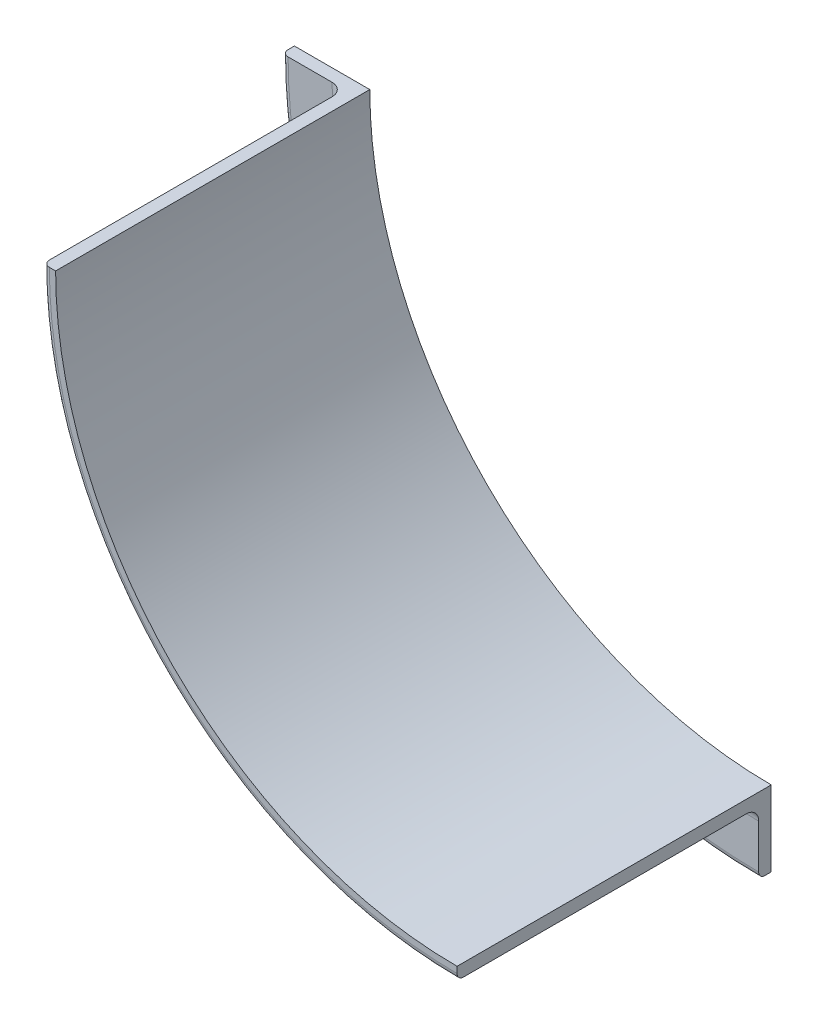
SolidWorks part; units mm, degrees
ref_plane "Front Plane" through (0, 0, 0) normal (0, 0, 1) x (1, 0, 0)
ref_plane "Top Plane" through (0, 0, 0) normal (0, 1, 0) x (1, 0, 0)
ref_plane "Right Plane" through (0, 0, 0) normal (1, 0, 0) x (0, 0, -1)
sketch "Sketch2" plane through (0, 0, 0) normal (0, 0, 1) x (1, 0, 0)
  line L0 (2758.9681, -672.5495) -> (2746.9681, -672.5495)
  line L1 (2822.8581, -736.4395) -> (2822.8581, -748.4395)
  arc A0 (2758.9681, -672.5495) -> (2822.8581, -736.4395) centre (2822.8581, -672.5495) ccw
  arc A1 (2746.9681, -672.5495) -> (2822.8581, -748.4395) centre (2822.8581, -672.5495) ccw
  dimension "D1" = 63.89
  dimension "D2" = 12
  dimension "D3" = 12
extrude "Boss-Extrude1" add sketch "Sketch2" along normal blind 50
sketch "Sketch3" plane through (0, 0, 50) normal (0, 0, 1) x (1, 0, 0)
  line L0 (2758.9681, -672.5495) -> (2746.9681, -672.5495) construction
  line L1 (2822.8581, -748.4395) -> (2822.8581, -736.4395) construction
  line L2 (2756.9681, -672.5495) -> (2737.4788, -672.5495)
  line L3 (2737.4788, -672.5495) -> (2737.4788, -757.5773)
  line L4 (2737.4788, -757.5773) -> (2822.8581, -757.5773)
  line L5 (2822.8581, -757.5773) -> (2822.8581, -738.4395)
  arc A0 (2756.9681, -672.5495) -> (2822.8581, -738.4395) centre (2822.8581, -672.5495) ccw
  dimension "D1" = 65.89
extrude "Cut-Extrude1" cut sketch "Sketch3" against normal blind 48
fillet "Fillet1" radius 1 2 edges at (2769.1958, -726.2118, 2) (2776.2669, -719.1407, 50)
fillet "Fillet2" radius 2 1 edges at (2776.2669, -719.1407, 2)
sketch "Sketch4" plane through (0, 0, 2) normal (0, 0, 1) x (1, 0, 0)
  line L1 (2754.9681, -672.5495) -> (2747.9681, -672.5495) construction
  line L2 (2822.8581, -747.4395) -> (2822.8581, -740.4395) construction
  circle A0 centre (2802.8581, -741.0807) radius 1.6
  circle A1 centre (2754.3269, -692.5495) radius 1.6
  arc A2 (2746.9681, -672.5495) -> (2822.8581, -748.4395) centre (2822.8581, -672.5495) ccw construction
  dimension "D1" = 3.2
  dimension "D2" = 3.2
  dimension "D3" = 71.39
  dimension "D4" = 71.39
  dimension "D5" = 20
  dimension "D6" = 20
extrude "Cut-Extrude2" cut sketch "Sketch4" against normal through all
